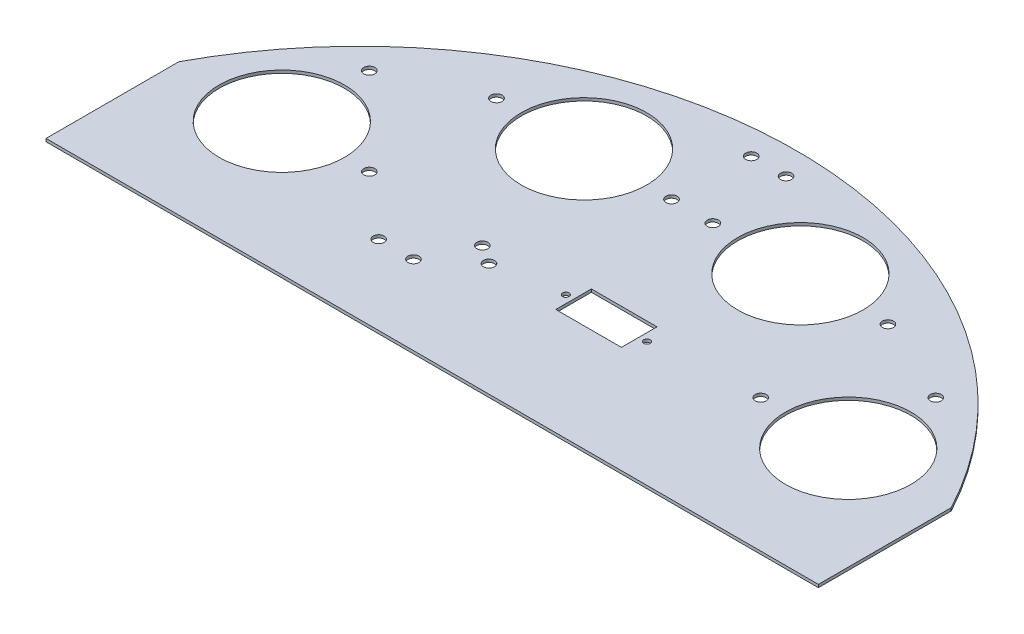
SolidWorks part; units mm, degrees
material "1060 Alloy"
ref_plane "Front Plane" through (0, 0, 0) normal (0, 0, 1) x (1, 0, 0)
ref_plane "Top Plane" through (0, 0, 0) normal (0, 1, 0) x (1, 0, 0)
ref_plane "Right Plane" through (0, 0, 0) normal (1, 0, 0) x (0, 0, -1)
sketch "Sketch3" plane through (0, 0, 0) normal (0, 1, 0) x (1, 0, 0)
  line L5 (-149.8445, -43.9726) -> (150.1555, -43.9726) construction
  line L6 (97.2375, 26.5616) -> (0.1555, -43.9726)
  line L7 (-86.3026, -18.9726) -> (-147.7465, -18.9726)
  line L8 (-132.2262, 26.5616) -> (-132.2262, -18.9726)
  line L9 (86.6136, -18.9726) -> (148.0575, -18.9726)
  line L10 (132.5372, 26.5616) -> (132.5372, -18.9726)
  line L11 (86.6136, -18.9726) -> (-86.3026, -18.9726)
  circle A10 centre (0.1555, -43.9726) radius 120 construction
  circle A11 centre (0.1555, -43.9726) radius 90 construction
  circle A12 centre (0.1555, -43.9726) radius 150
  circle A13 centre (97.2375, 26.5616) radius 21.5
  circle A14 centre (37.2375, 70.1542) radius 21.5
  circle A15 centre (-36.9265, 70.1542) radius 21.5
  circle A16 centre (-96.9265, 26.5616) radius 21.5
  point P5 (0.1555, -43.9726)
  point P9 (0.1555, -43.9726)
  point P22 (0.1555, -43.9726)
  dimension "D3" = 300
  dimension "D7" = 43
  dimension "D4" = 36
  dimension "D5" = 4
  dimension "D2" = 240
  dimension "D1" = 180
  dimension "D6" = 25
extrude "Boss-Extrude3" add sketch "Sketch3" along normal blind 1
sketch "Sketch5" plane through (0, 1, 0) normal (0, 1, 0) x (1, 0, 0)
  line L0 (37.2375, 70.1542) -> (-36.9265, 70.1542) construction
  line L1 (-36.9265, 70.1542) -> (-96.9265, 26.5616) construction
  line L2 (37.2375, 70.1542) -> (97.2375, 26.5616) construction
  circle A0 centre (97.2375, 26.5616) radius 30 construction
  circle A1 centre (37.2375, 70.1542) radius 30 construction
  circle A2 centre (-36.9265, 70.1542) radius 30 construction
  circle A3 centre (-96.9265, 26.5616) radius 30 construction
  point P12 (67.2375, 26.5616)
  point P13 (97.2375, 56.5616)
  point P14 (7.2375, 70.1542)
  point P15 (67.2375, 70.1542)
  point P16 (-6.9265, 70.1542)
  point P17 (-66.9265, 70.1542)
  point P18 (-96.9265, 56.5616)
  point P19 (-66.9265, 26.5616)
sketch "Sketch10" plane through (0, 0, 0) normal (0, -1, 0) x (-1, 0, 0)
  line L0 (-28.4264, 17.6232) -> (-16.5209, 17.6232)
  line L1 (-27.5764, 17.6232) -> (-6.7764, 17.6232) construction
  line L2 (-28.4264, 17.6232) -> (-28.4264, 29.8232)
  line L3 (-28.4264, 29.8232) -> (-5.9264, 29.8232)
  line L4 (-5.9264, 29.8232) -> (-5.9264, 17.6232)
  line L5 (-5.9264, 17.6232) -> (-28.4264, 17.6232)
  line L6 (-5.9264, 18.4732) -> (-5.9264, 28.9732) construction
  line L7 (-6.7764, 29.8232) -> (-27.5764, 29.8232) construction
  line L8 (-28.4264, 28.9732) -> (-28.4264, 18.4732) construction
  line L9 (43.9148, 8.1232) -> (26.8038, 8.1232) construction
  line L10 (4.3576, 96.6113) -> (-7.7151, 96.6113) construction
  line L11 (-0.0313, 92.8613) -> (-0.0264, 100.3613) construction
  line L12 (39.2014, 4.3732) -> (39.2014, 11.8732) construction
  line L13 (32.1421, 28.2546) -> (19.1543, 19.7949) construction
  line L14 (28.105, 20.253) -> (21.0773, 31.0423) construction
  circle A0 centre (-0.0264, 100.3613) radius 2.5 construction
  circle A1 centre (-0.0313, 92.8613) radius 2.5 construction
  circle A2 centre (39.2014, 4.3732) radius 2.5 construction
  circle A3 centre (39.2014, 11.8732) radius 2.5 construction
  circle A4 centre (19.1543, 19.7949) radius 2.5 construction
  circle A5 centre (32.1421, 28.2546) radius 2.5 construction
  circle A6 centre (-31.0764, 23.7232) radius 1.1
  circle A7 centre (-3.2764, 23.7232) radius 1.1
  dimension "D1" = 3.75
  dimension "D2" = 3.75
  dimension "D3" = 7.75
extrude "Cut-Extrude3" cut sketch "Sketch10" against normal through all contours L5 L4 L3 L2 L0 | A5 | A4 | A3 | A2 | A1 | A0 | A6 | A7
hole_wizard "#6 Clearance Hole1" positions "Sketch8" profile "Sketch9" hole size "#6" standard "ANSI Inch" end condition through all
sketch "Sketch8" plane through (0, 0, 0) normal (0, -1, 0) x (-1, 0, 0)
  line L0 (43.9148, 8.1232) -> (26.8038, 8.1232) construction
  line L1 (39.2014, 4.3732) -> (39.2014, 11.8732) construction
  line L2 (4.3576, 96.6113) -> (-7.7151, 96.6113) construction
  line L3 (-0.0313, 92.8613) -> (-0.0264, 100.3613) construction
  line L4 (32.1421, 28.2546) -> (19.1543, 19.7949) construction
  point P0 (-97.2375, 56.5616)
  point P2 (-67.2375, 26.5616)
  point P4 (-67.2375, 70.1542)
  point P6 (-7.2375, 70.1542)
  point P8 (6.9265, 70.1542)
  point P10 (66.9265, 70.1542)
  point P12 (96.9265, 56.5616)
  point P14 (66.9265, 26.5616)
  point P50 (19.1543, 19.7949)
  point P53 (45.2914, 8.1232)
  point P55 (33.3614, 8.1232)
  point P75 (6.0611, 96.6113)
  point P79 (-5.8689, 96.6113)
  point P84 (25.6482, 24.0247)
  point P89 (0, 0)
  dimension "D1" = 6.09
  dimension "D2" = 5.84
  dimension "D3" = 6.09
  dimension "D4" = 5.84
sketch "Sketch9" plane through (97.2375, 0, -56.5616) normal (1, 0, 0) x (0, 0, -1)
  line L0 (0, 0) -> (0, 1)
  line L1 (0, 1) -> (1.8986, 1)
  line L2 (1.8986, 1) -> (1.8986, 0)
  line L5 (1.8986, 0) -> (0, 0)
  line L11 (0, -6.35) -> (0, 107.95) construction
  dimension "Thru Hole Dia." = 3.7973
  dimension "Thru Hole Depth" = 1
